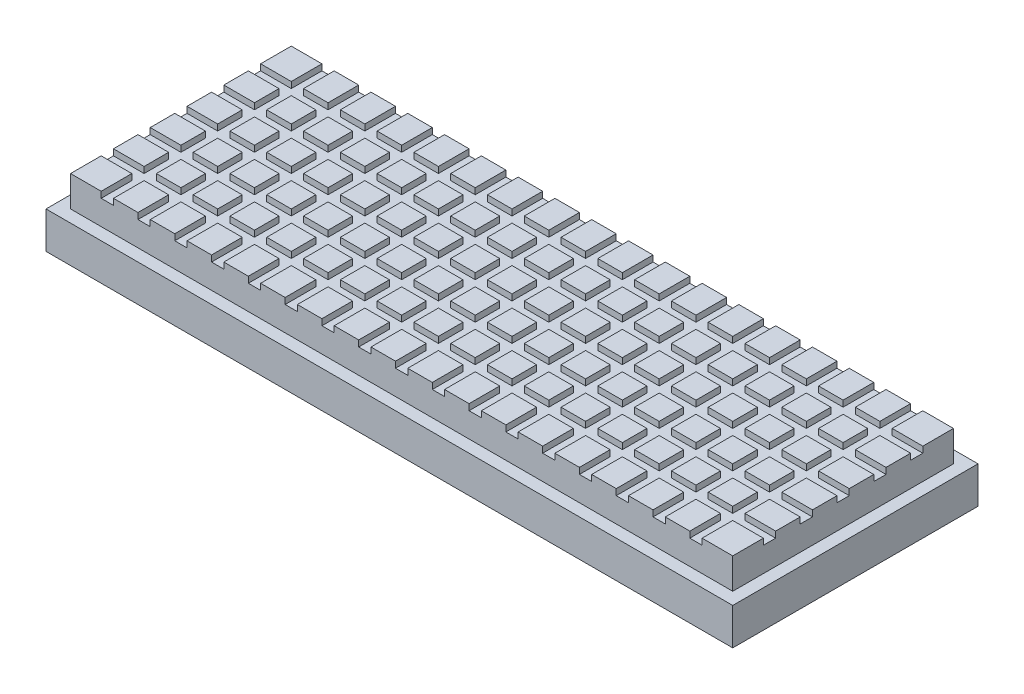
SolidWorks part; units mm, degrees
ref_plane "Front Plane" through (0, 0, 0) normal (0, 0, 1) x (1, 0, 0)
ref_plane "Top Plane" through (0, 0, 0) normal (0, 1, 0) x (1, 0, 0)
ref_plane "Right Plane" through (0, 0, 0) normal (1, 0, 0) x (0, 0, -1)
sketch "Sketch1" plane through (0, 0, 0) normal (0, 1, 0) x (1, 0, 0)
  line L1 (-177.8, -63.5) -> (177.8, -63.5)
  line L2 (-177.8, -63.5) -> (-177.8, 63.5)
  line L3 (-177.8, 63.5) -> (177.8, 63.5)
  line L4 (177.8, -63.5) -> (177.8, 63.5)
  line L5 (-177.8, -63.5) -> (177.8, 63.5) construction
  line L6 (-177.8, 63.5) -> (177.8, -63.5) construction
  point P0 (0, 0)
  dimension "D1" = 355.6
  dimension "D2" = 127
extrude "Boss-Extrude1" add sketch "Sketch1" along normal blind 19.05
sketch "Sketch2" plane through (0, 19.05, 0) normal (0, 1, 0) x (1, 0, 0)
  line L1 (-171.45, -57.15) -> (171.45, -57.15)
  line L2 (-171.45, -57.15) -> (-171.45, 57.15)
  line L3 (-171.45, 57.15) -> (171.45, 57.15)
  line L4 (171.45, -57.15) -> (171.45, 57.15)
  line L5 (-171.45, -57.15) -> (171.45, 57.15) construction
  line L6 (-171.45, 57.15) -> (171.45, -57.15) construction
  point P0 (0, 0)
  dimension "D1" = 342.9
  dimension "D2" = 114.3
extrude "Boss-Extrude2" add sketch "Sketch2" along normal blind 15.875
sketch "Sketch3" plane through (0, 34.925, 0) normal (0, 1, 0) x (1, 0, 0)
  line L0 (171.45, 57.15) -> (-171.45, 57.15) construction
  line L1 (-3.175, -57.15) -> (3.175, -57.15)
  line L2 (-3.175, -57.15) -> (-3.175, 57.15)
  line L3 (-3.175, 57.15) -> (3.175, 57.15)
  line L4 (3.175, -57.15) -> (3.175, 57.15)
  line L5 (-3.175, -57.15) -> (3.175, 57.15) construction
  line L6 (-3.175, 57.15) -> (3.175, -57.15) construction
  point P0 (0, 0)
  dimension "D1" = 6.35
extrude "Cut-Extrude1" cut sketch "Sketch3" against normal blind 3.175
pattern_linear "LPattern1" count 9 spacing 19.05 along (-1, 0, 0) count 9 spacing 19.05 along (1, 0, 0) of "Cut-Extrude1"
sketch "Sketch4" plane through (0, 34.925, 0) normal (0, 1, 0) x (1, 0, 0)
  line L0 (171.45, -57.15) -> (171.45, 57.15) construction
  line L1 (-171.45, -3.175) -> (171.45, -3.175)
  line L2 (-171.45, -3.175) -> (-171.45, 3.175)
  line L3 (-171.45, 3.175) -> (171.45, 3.175)
  line L4 (171.45, -3.175) -> (171.45, 3.175)
  line L5 (-171.45, -3.175) -> (171.45, 3.175) construction
  line L6 (-171.45, 3.175) -> (171.45, -3.175) construction
  point P0 (0, 0)
  dimension "D1" = 6.35
extrude "Cut-Extrude2" cut sketch "Sketch4" against normal blind 3.175
pattern_linear "LPattern2" count 3 spacing 19.05 along (0, 0, -1) count 3 spacing 19.05 along (0, 0, 1) of "Cut-Extrude2"
